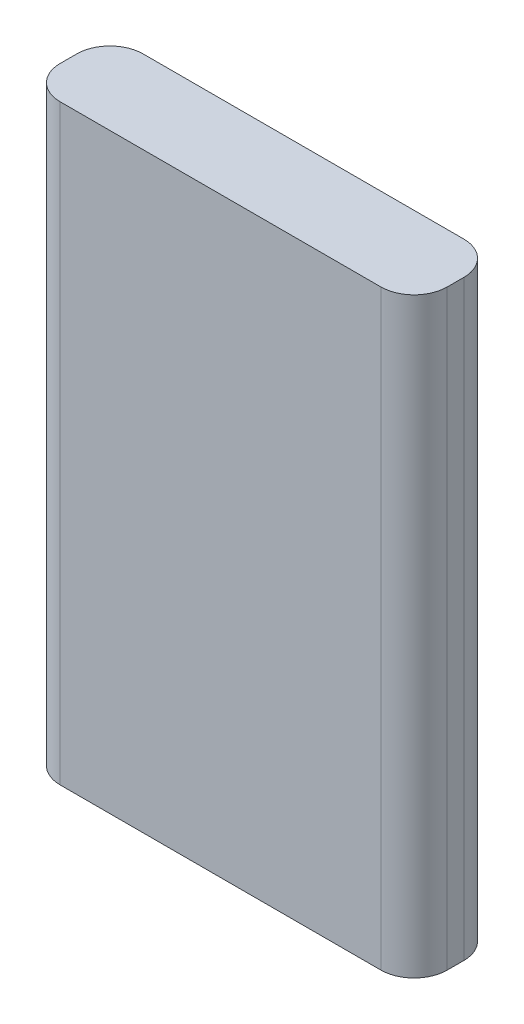
SolidWorks part; units mm, degrees
ref_plane "Alzado" through (0, 0, 0) normal (0, 0, 1) x (1, 0, 0)
ref_plane "Planta" through (0, 0, 0) normal (0, 1, 0) x (1, 0, 0)
ref_plane "Vista lateral" through (0, 0, 0) normal (1, 0, 0) x (0, 0, -1)
sketch "Croquis1" plane through (0, 0, 0) normal (0, 0, 1) x (1, 0, 0)
  line L1 (17.5, -26.75) -> (-17.5, -26.75)
  line L2 (17.5, -26.75) -> (17.5, 26.75)
  line L3 (17.5, 26.75) -> (-17.5, 26.75)
  line L4 (-17.5, -26.75) -> (-17.5, 26.75)
  line L5 (17.5, -26.75) -> (-17.5, 26.75) construction
  line L6 (17.5, 26.75) -> (-17.5, -26.75) construction
  point P0 (0, 0)
  dimension "D1" = 53.5
  dimension "D2" = 35
extrude "Saliente-Extruir1" add sketch "Croquis1" along normal blind 7.5
fillet "Redondeo1" radius 3 4 edges at (-17.5, 0, 0) (-17.5, 0, 7.5) (17.5, 0, 0) (17.5, 0, 7.5)
